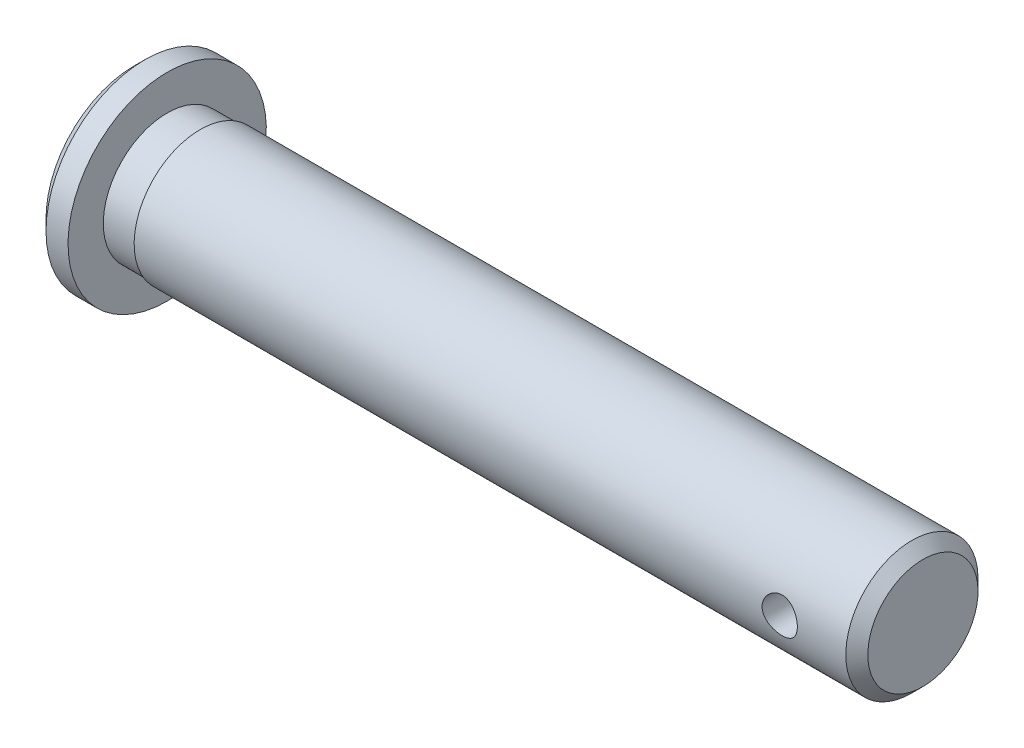
SolidWorks part; units mm, degrees
ref_plane "Front Plane" through (0, 0, 0) normal (0, 0, 1) x (1, 0, 0)
ref_plane "Top Plane" through (0, 0, 0) normal (0, 1, 0) x (1, 0, 0)
ref_plane "Right Plane" through (0, 0, 0) normal (1, 0, 0) x (0, 0, -1)
sketch "Sketch1" plane through (0, 0, 0) normal (0, 0, 1) x (1, 0, 0)
  line L0 (0, 0) -> (34.3, 0) construction
  line L1 (-1.5, 0) -> (-1.5, 4.5)
  line L2 (-1.5, 4.5) -> (0, 4.5)
  line L3 (0, 4.5) -> (0, 2.9)
  line L4 (0, 2.9) -> (1.5, 2.9)
  line L5 (34.3, 3) -> (34.3, 0)
  line L6 (34.3, 0) -> (-1.5, 0)
  line L7 (1.5, 2.9) -> (1.5, 3)
  line L8 (1.5, 3) -> (34.3, 3)
  line L9 (30, 3) -> (30, 0) construction
  line L10 (30.8, 0) -> (30.8, 3) construction
  point P2 (30.8, 0)
  dimension "H" = 9
  dimension "T" = 1.5
  dimension "L1_1" = 35.8
  dimension "D" = 6
  dimension "N_s" = 1.5
  dimension "U_s" = 5.8
  dimension "L" = 30
  dimension "N" = 3.5
  dimension "D1" = 0.8
revolve "Revolve1" add sketch "Sketch1" angle 360 about L0
ref_plane "Plane1" through (0, 0, 3) normal (0, 0, 1) x (1, 0, 0)
sketch "Sketch2" plane through (0, 0, 3) normal (0, 0, 1) x (1, 0, 0)
  line L2 (34.3, -3) -> (34.3, 3) construction
  circle A0 centre (30.8, 0) radius 0.8
  point P5 (30, 0)
  dimension "N" = 3.5
  dimension "D_s" = 1.6
extrude "Cut-Extrude1" cut sketch "Sketch2" against normal through all
chamfer "Chamfer1" distance 0.5 angle 45 2 edges at (34.3, -3, 0) (-1.5, -4.5, 0)
sketch "Sketch3" [suppressed] plane through (0, 0, 0) normal (0, 0, 1) x (1, 0, 0)
  line L0 (-1.5, 0) -> (12.9, 0) construction
  line L1 (-1.5, 2.25) -> (-1.5, -2.25) construction
  line L2 (12.9, -1) -> (12.9, 1) construction
  line L3 (0, -2.75) -> (0, 2.75) construction
  line L4 (12.9, 0) -> (0, 0)
  line L5 (12.9, 0) -> (12.9, 1.5)
  line L6 (12.9, 1.5) -> (0, 1.5)
  line L7 (0, 0) -> (0, 1.5)
  dimension "D" = 6
revolve "Cut-Revolve2" [suppressed] cut sketch "Sketch3" angle 360 about L0
sketch "Sketch4" [suppressed] plane through (0, 0, 0) normal (0, 0, 1) x (1, 0, 0)
  line L0 (-1.5, 0) -> (11.9, 0) construction
  line L1 (-1.5, 2.25) -> (-1.5, -2.25) construction
  line L3 (1.5, 1.5) -> (1.5, 1.45)
  line L4 (0, 0) -> (11.9, 0)
  line L5 (0, 0) -> (0, 1.45)
  line L6 (1.5, 1.5) -> (11.9, 1.5)
  line L7 (11.9, 0) -> (11.9, 1.5)
  line L8 (1.5, 1.45) -> (0, 1.45)
  line L9 (10.4, 1.5) -> (10.4, 0) construction
  line L10 (10, 1.5) -> (10, 0) construction
  line L11 (0, -2.75) -> (0, 2.75) construction
  dimension "D" = 6
  dimension "N_s" = 1.5
  dimension "U_s" = 5.8
  dimension "L" = 30
  dimension "D1" = 0.8
  dimension "NC" = 1.5
  dimension "L1_2" = 13.4
revolve "Revolve2" [suppressed] add sketch "Sketch4" angle 360 about L0
sketch "Sketch5" [suppressed] plane through (0, 0, 1.5) normal (0, 0, 1) x (1, 0, 0)
  line L0 (0, 0) -> (11.9, 0) construction
  line L3 (11.9, -1.5) -> (11.9, 1.5) construction
  circle A0 centre (10.4, 0) radius 0.4
  dimension "D_s" = 1.6
  dimension "NC" = 1.5
extrude "Cut-Extrude2" [suppressed] cut sketch "Sketch5" against normal through all
chamfer "Chamfer2" [suppressed] distance 0.5 angle 45
sketch "Sketch6" [suppressed] plane through (0, 0, 0) normal (0, 0, 1) x (1, 0, 0)
  line L0 (-1.5, 2.25) -> (-1.5, -2.25) construction
  line L1 (-1.5, 2.75) -> (0, 2.75)
  line L2 (-1.5, 2.75) -> (-1.5, 0)
  line L3 (-1.5, 0) -> (0, 0)
  line L4 (0, 2.75) -> (0, 0)
  line L6 (0, -2.75) -> (0, 2.75) construction
  line L7 (0, 0) -> (-1.5, 0) construction
  dimension "H" = 9
revolve "Cut-Revolve3" [suppressed] cut sketch "Sketch6" angle 360 about L7
sketch "Sketch7" [suppressed] plane through (0, 0, 0) normal (0, 0, 1) x (1, 0, 0)
  line L1 (-2, 2.75) -> (0, 2.75)
  line L2 (-2, 2.75) -> (-2, 0)
  line L3 (-2, 0) -> (0, 0)
  line L4 (0, 2.75) -> (0, 0)
  line L5 (0, 1.45) -> (0, -1.45) construction
  line L7 (0, 0) -> (-2, 0) construction
  line L8 (12.9, -1) -> (12.9, 1) construction
  dimension "H" = 9
  dimension "L1_3" = 14.9
  dimension "TC" = 2
revolve "Revolve3" [suppressed] add sketch "Sketch7" angle 360 about L7
chamfer "Chamfer3" [suppressed] distance 0.5 angle 45
sketch "Sketch8" [suppressed] plane through (0, 0, 0) normal (0, 0, 1) x (1, 0, 0)
  line L0 (0, 1.45) -> (0, -1.45) construction
  line L1 (-2, 2.75) -> (0, 2.75)
  line L2 (-2, 2.75) -> (-2, 0)
  line L3 (-2, 0) -> (0, 0)
  line L4 (0, 2.75) -> (0, 0)
  line L5 (11.9, -1) -> (11.9, 1) construction
  line L7 (0, 0) -> (-2, 0) construction
  dimension "H" = 9
  dimension "L1_4" = 13.9
  dimension "TC" = 2
revolve "Revolve5" [suppressed] add sketch "Sketch8" angle 360 about L7
chamfer "Chamfer4" [suppressed] distance 0.5 angle 45
sketch "Sketch9" [suppressed] plane through (0, 0, 0) normal (1, 0, 0) x (0, 0, -1)
  line L0 (0, 0) -> (-2.75, 0) construction
  line L1 (-2.75, 2.75) -> (-1.75, 2.75)
  line L2 (-2.75, 2.75) -> (-2.75, -2.75)
  line L3 (-2.75, -2.75) -> (-1.75, -2.75)
  line L4 (-1.75, 2.75) -> (-1.75, -2.75)
  dimension "H" = 9
  dimension "HC" = 3.5
  dimension "D2" = 4.5
extrude "Cut-Extrude3" [suppressed] cut sketch "Sketch9" against normal through all
equation "\"Plane dim\"= \"D@Sketch1\" * 0.5"
equation "\"D1@Sketch4\" = \"D_s@Sketch2\" / 2"
equation "\"HC@Sketch9\"=if ( \"D@Sketch1\" > 10 , \"H@Sketch1\" / 2 - 2 , \"H@Sketch1\" / 2 - 1 )"
equation "\"D2@Sketch9\"=\"H@Sketch1\"/2"
equation "\"D1@Sketch1\"=\"D_s@Sketch2\"/2"
